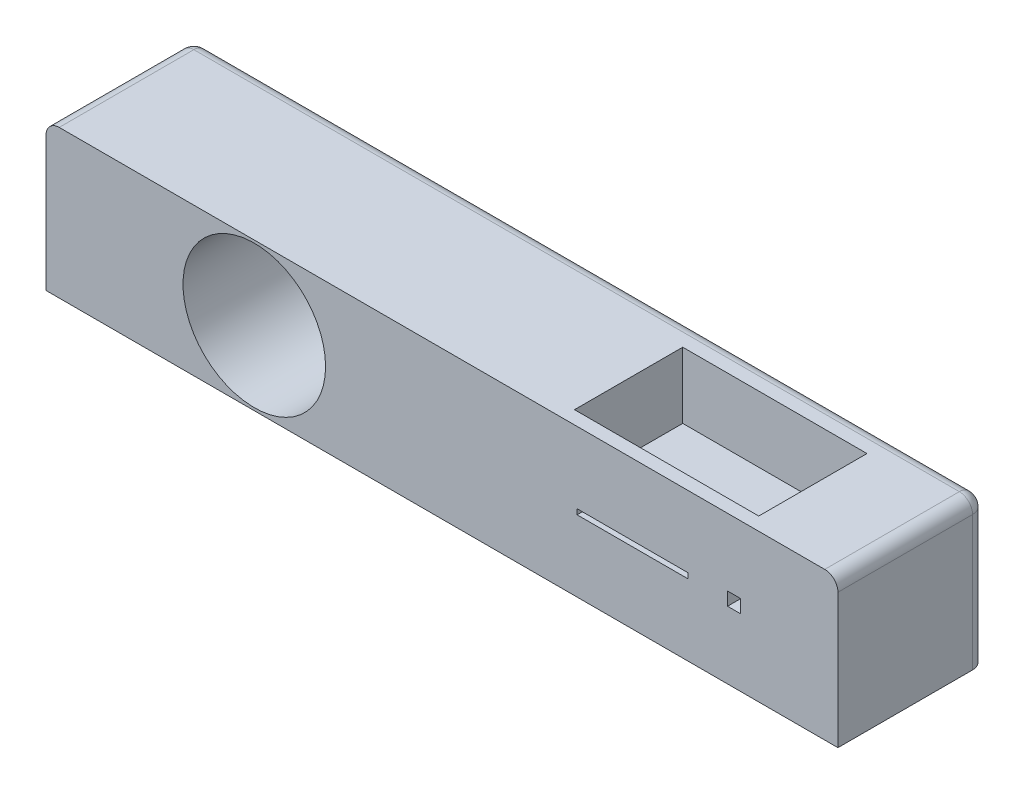
SolidWorks part; units mm, degrees
ref_plane "Front Plane" through (0, 0, 0) normal (0, 0, 1) x (1, 0, 0)
ref_plane "Top Plane" through (0, 0, 0) normal (0, 1, 0) x (1, 0, 0)
ref_plane "Right Plane" through (0, 0, 0) normal (1, 0, 0) x (0, 0, -1)
sketch "Sketch1" plane through (0, 0, 0) normal (0, 0, 1) x (1, 0, 0)
  line L1 (-150, -28) -> (150, -28)
  line L2 (-150, -28) -> (-150, 28)
  line L3 (-150, 28) -> (150, 28)
  line L4 (150, -28) -> (150, 28)
  line L5 (-150, -28) -> (150, 28) construction
  line L6 (-150, 28) -> (150, -28) construction
  point P0 (0, 0)
  dimension "D1" = 300
  dimension "D2" = 56
extrude "Boss-Extrude1" add sketch "Sketch1" along normal blind 56
fillet "Fillet1" radius 5 5 edges at (0, 28, 0) (-150, 0, 0) (-150, 28, 28) (150, 0, 0) (150, 28, 28)
sketch "Sketch2" plane through (0, 0, 56) normal (0, 0, 1) x (1, 0, 0)
  line L0 (-126.03, 0) -> (150.0113, 0) construction
  line L3 (-126.03, 28) -> (-126.03, -28) construction
  line L4 (145, 28) -> (-145, 28) construction
  line L5 (-150, -28) -> (150, -28) construction
  line L7 (51.1823, 1) -> (93.1823, 1)
  line L8 (51.1823, 1) -> (51.1823, -1)
  line L9 (51.1823, -1) -> (93.1823, -1)
  line L10 (93.1823, 1) -> (93.1823, -1)
  line L11 (51.1823, 1) -> (93.1823, -1) construction
  line L12 (51.1823, -1) -> (93.1823, 1) construction
  line L13 (108.1823, 2.5) -> (113.1823, 2.5)
  line L14 (108.1823, 2.5) -> (108.1823, -2.5)
  line L15 (108.1823, -2.5) -> (113.1823, -2.5)
  line L16 (113.1823, 2.5) -> (113.1823, -2.5)
  line L17 (108.1823, 2.5) -> (113.1823, -2.5) construction
  line L18 (108.1823, -2.5) -> (113.1823, 2.5) construction
  circle A0 centre (-71.0954, 0) radius 27
  point P4 (0, 0)
  point P6 (3.9992, 0)
  point P8 (110.6823, 0)
  point P18 (-126.03, 0)
  point P23 (0, 0)
  point P24 (3.9992, 0)
  point P25 (39.8948, -0.4524)
  point P26 (0, 0)
  point P27 (110.9134, 0)
  point P28 (72.1823, 0)
  point P31 (80.9711, -0.5407)
  dimension "D1" = 54
  dimension "D2" = 2
  dimension "D3" = 42
  dimension "D4" = 5
  dimension "D5" = 5
  dimension "D6" = 15
extrude "Cut-Extrude1" cut sketch "Sketch2" against normal offset from surface (50 mm away) 6 up to face at (0, -2.5, 0)
sketch "Sketch3" plane through (0, 28, 0) normal (0, 1, 0) x (1, 0, 0)
  line L0 (145, -56) -> (-145, -56) construction
  line L1 (115, -51) -> (45.2096, -51)
  line L2 (115, -51) -> (115, -10)
  line L3 (115, -10) -> (45.2096, -10)
  line L4 (45.2096, -51) -> (45.2096, -10)
  line L5 (145, -5) -> (-145, -5) construction
  line L6 (145, -56) -> (145, -5) construction
  dimension "D1" = 5
  dimension "D2" = 5
  dimension "D3" = 30
extrude "Cut-Extrude2" cut sketch "Sketch3" against normal offset from surface (25 mm away) 2 up to face at (72.1823, 1, 31)
